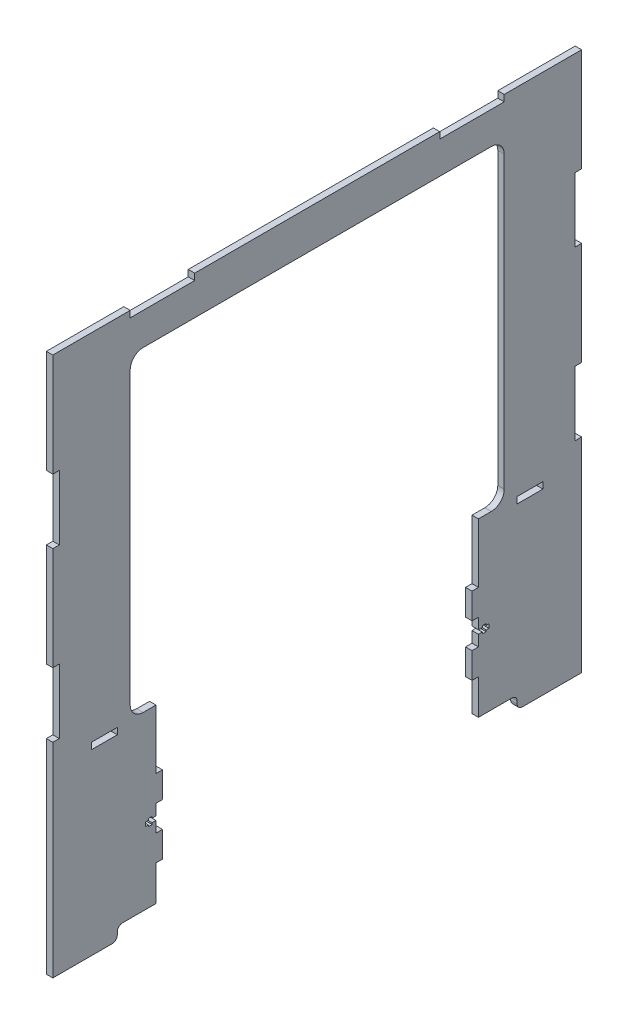
SolidWorks part; units mm, degrees
ref_plane "前视基准面" through (0, 0, 0) normal (0, 0, 1) x (1, 0, 0)
ref_plane "上视基准面" through (0, 0, 0) normal (0, 1, 0) x (1, 0, 0)
ref_plane "右视基准面" through (0, 0, 0) normal (1, 0, 0) x (0, 0, -1)
sketch "草图1" plane through (0, 0, 0) normal (1, 0, 0) x (0, 0, -1)
  line L0 (-80, 27) -> (-80, -19)
  line L1 (-330, -39) -> (-330, -47.5)
  line L2 (0, 0) -> (0, 42)
  line L3 (0, 302) -> (-60, 302)
  line L4 (-410, -90.3) -> (-410, 42)
  line L5 (-340, 272) -> (-70, 272)
  line L6 (-350, 262) -> (-350, 37)
  line L7 (-340, 27) -> (-330, 27)
  line L8 (-60, 262) -> (-60, 37)
  line L9 (-330, 27) -> (-330, -19)
  line L10 (-80, 27) -> (-70, 27)
  line L11 (-330, -19) -> (-325, -19)
  line L12 (-410, 222) -> (-410, 302)
  line L13 (0, 222) -> (-5, 222)
  line L14 (-80, -79) -> (-80, -90.3)
  line L15 (0, 172) -> (-5, 172)
  line L16 (-5, 222) -> (-5, 172)
  line L17 (0, 92) -> (-5, 92)
  line L18 (0, 222) -> (0, 302)
  line L19 (0, 42) -> (-5, 42)
  line L20 (-5, 92) -> (-5, 42)
  line L21 (-410, 92) -> (-405, 92)
  line L22 (0, 92) -> (0, 172)
  line L23 (-410, 42) -> (-405, 42)
  line L24 (-405, 92) -> (-405, 42)
  line L25 (-410, 222) -> (-405, 222)
  line L26 (-410, 92) -> (-410, 172)
  line L27 (-410, 172) -> (-405, 172)
  line L28 (-405, 222) -> (-405, 172)
  line L29 (-50, 27) -> (-30, 27)
  line L30 (-50, 27) -> (-50, 22)
  line L31 (-50, 22) -> (-30, 22)
  line L32 (-30, 27) -> (-30, 22)
  line L33 (-360, 27) -> (-380, 27)
  line L34 (-360, 27) -> (-360, 22)
  line L35 (-360, 22) -> (-380, 22)
  line L36 (-380, 27) -> (-380, 22)
  line L37 (-330, -39) -> (-325, -39)
  line L38 (-110, 302) -> (-300, 302)
  line L39 (-350, 302) -> (-410, 302)
  line L40 (-60, 302) -> (-60, 297)
  line L41 (-325, -19) -> (-325, -39)
  line L42 (-60, 297) -> (-110, 297)
  line L43 (-330, -59) -> (-325, -59)
  line L44 (-80, -39) -> (-80, -47.5)
  line L45 (-330, -79) -> (-325, -79)
  line L46 (-110, 302) -> (-110, 297)
  line L47 (-325, -59) -> (-325, -79)
  line L48 (-80, -19) -> (-85, -19)
  line L49 (0, -64.3) -> (0, -116.3)
  line L50 (-350, 302) -> (-350, 297)
  line L51 (-350, 297) -> (-300, 297)
  line L52 (-300, 302) -> (-300, 297)
  line L53 (-80, -39) -> (-85, -39)
  line L54 (-85, -19) -> (-85, -39)
  line L55 (-80, -106.3) -> (-54, -106.3)
  line L56 (-80, -59) -> (-85, -59)
  line L57 (0, -116.3) -> (-46, -116.3)
  line L58 (-80, -79) -> (-85, -79)
  line L59 (-85, -59) -> (-85, -79)
  line L60 (-330, -79) -> (-330, -90.3)
  line L61 (-80, -106.3) -> (-80, -90.3)
  line L62 (-330, -90.3) -> (-330, -106.3)
  line L63 (-364, -116.3) -> (-410, -116.3)
  line L64 (-50, -110.3) -> (-50, -112.3)
  line L65 (0, -64.3) -> (0, 0)
  line L66 (-410, -116.3) -> (-410, -90.3)
  line L67 (-330, -106.3) -> (-356, -106.3)
  line L68 (-360, -110.3) -> (-360, -112.3)
  line L69 (-330, -47.5) -> (-333, -47.5)
  line L70 (-333, -47.5) -> (-333, -46.25)
  line L71 (-333, -46.25) -> (-336, -46.25)
  line L72 (-336, -46.25) -> (-336, -47.5)
  line L73 (-336, -47.5) -> (-338, -47.5)
  line L74 (-338, -47.5) -> (-338, -50.5)
  line L75 (-338, -50.5) -> (-336, -50.5)
  line L76 (-336, -50.5) -> (-336, -51.75)
  line L77 (-336, -51.75) -> (-333, -51.75)
  line L78 (-333, -51.75) -> (-333, -50.5)
  line L79 (-330, -50.5) -> (-333, -50.5)
  line L80 (-330, -50.5) -> (-330, -59)
  line L81 (-80, -47.5) -> (-77, -47.5)
  line L82 (-77, -47.5) -> (-77, -46.25)
  line L83 (-77, -46.25) -> (-74, -46.25)
  line L84 (-74, -46.25) -> (-74, -47.5)
  line L85 (-74, -47.5) -> (-72, -47.5)
  line L86 (-72, -47.5) -> (-72, -50.5)
  line L87 (-72, -50.5) -> (-74, -50.5)
  line L88 (-74, -50.5) -> (-74, -51.75)
  line L89 (-74, -51.75) -> (-77, -51.75)
  line L90 (-77, -51.75) -> (-77, -50.5)
  line L91 (-77, -50.5) -> (-80, -50.5)
  line L92 (-80, -50.5) -> (-80, -59)
  arc A0 (-360, -112.3) -> (-364, -116.3) centre (-364, -112.3) cw
  arc A1 (-50, -112.3) -> (-46, -116.3) centre (-46, -112.3) ccw
  arc A2 (-70, 272) -> (-60, 262) centre (-70, 262) cw
  arc A3 (-340, 272) -> (-350, 262) centre (-340, 262) ccw
  arc A4 (-70, 27) -> (-60, 37) centre (-70, 37) ccw
  arc A5 (-350, 37) -> (-340, 27) centre (-340, 37) ccw
  arc A6 (-356, -106.3) -> (-360, -110.3) centre (-356, -110.3) ccw
  arc A7 (-54, -106.3) -> (-50, -110.3) centre (-54, -110.3) cw
  point P31 (0, 0)
  point P75 (-75, 27)
  dimension "D21" = 80
  dimension "D22" = 10
  dimension "D53" = 4
  dimension "D4" = 80
  dimension "D6" = 60
  dimension "D7" = 60
  dimension "D8" = 30
  dimension "D9" = 5
  dimension "D10" = 5
  dimension "D11" = 5
  dimension "D12" = 5
  dimension "D13" = 50
  dimension "D14" = 50
  dimension "D15" = 50
  dimension "D16" = 50
  dimension "D17" = 80
  dimension "D18" = 80
  dimension "D19" = 80
  dimension "D20" = 80
  dimension "D23" = 20
  dimension "D24" = 5
  dimension "D25" = 0
  dimension "D26" = 5
  dimension "D27" = 20
  dimension "D28" = 30
  dimension "D29" = 30
  dimension "D30" = 143.3
  dimension "D31" = 5
  dimension "D32" = 5
  dimension "D33" = 5
  dimension "D34" = 275
  dimension "D35" = 5
  dimension "D36" = 410
  dimension "D37" = 5
  dimension "D38" = 50
  dimension "D39" = 60
  dimension "D40" = 50
  dimension "D41" = 5
  dimension "D42" = 60
  dimension "D43" = 20
  dimension "D44" = 20
  dimension "D45" = 20
  dimension "D46" = 20
  dimension "D47" = 20
  dimension "D48" = 46
  dimension "D49" = 143.3
  dimension "D50" = 46
  dimension "D51" = 20
  dimension "D52" = 0
  dimension "D54" = 3
  dimension "D55" = 1.25
  dimension "D56" = 1.25
  dimension "D57" = 1.25
  dimension "D58" = 1.25
  dimension "D59" = 5.5
  dimension "D60" = 3
  dimension "D61" = 8.5
extrude "凸台-拉伸1" add sketch "草图1" along normal blind 5
